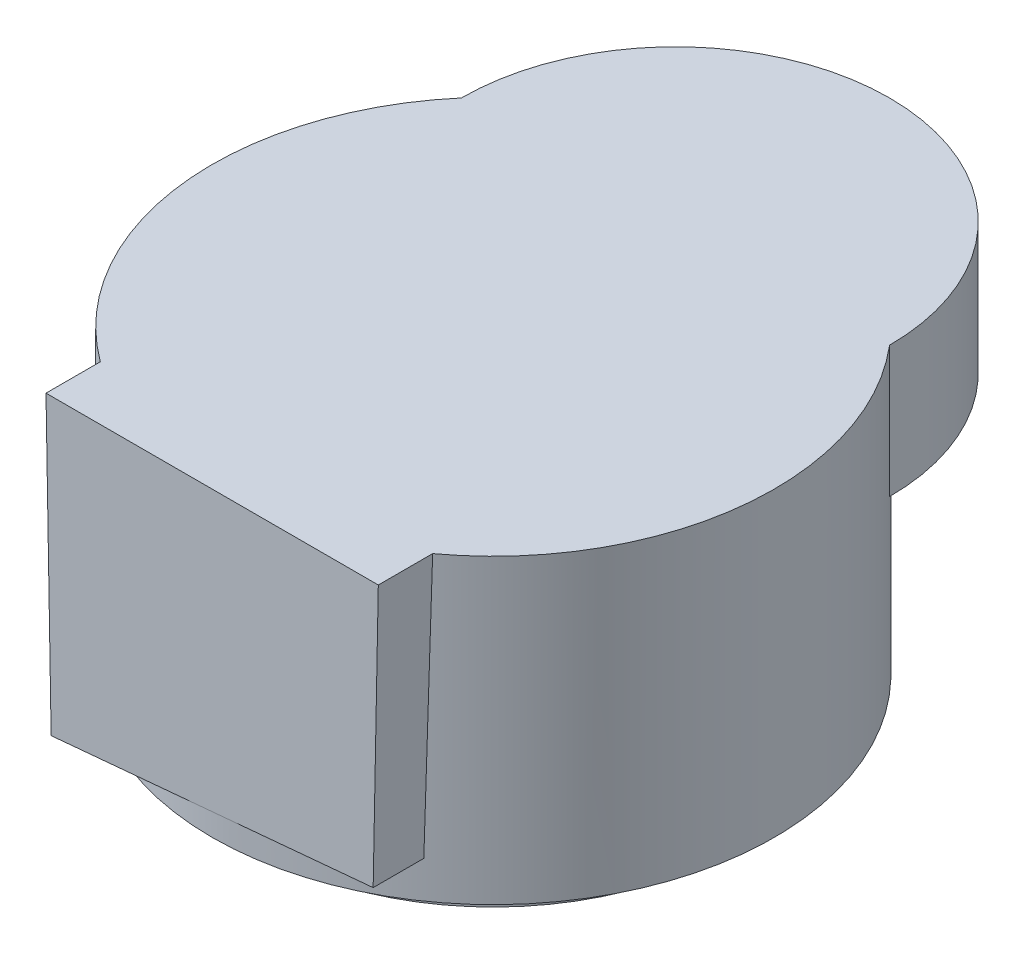
SolidWorks part; units mm, degrees
ref_plane "Alzado" through (0, 0, 0) normal (0, 0, 1) x (1, 0, 0)
ref_plane "Planta" through (0, 0, 0) normal (0, 1, 0) x (1, 0, 0)
ref_plane "Vista lateral" through (0, 0, 0) normal (1, 0, 0) x (0, 0, -1)
sketch "Croquis1" plane through (0, 0, 0) normal (0, 1, 0) x (1, 0, 0)
  circle A0 centre (0, 0) radius 9.56 construction
  circle A1 centre (0, 0) radius 8.035
  dimension "D1" = 19.12
  dimension "D2" = 16.07
extrude "Saliente-Extruir1" add sketch "Croquis1" along normal blind 1.15
sketch "Croquis2" plane through (0, 1.15, 0) normal (0, 1, 0) x (1, 0, 0)
  circle A0 centre (0, 0) radius 9.56 construction
  circle A1 centre (0, 0) radius 9.56
extrude "Saliente-Extruir2" add sketch "Croquis2" along normal blind 10.26
sketch "Croquis3" plane through (0, 11.41, 0) normal (0, 1, 0) x (1, 0, 0)
  arc A0 (-7.28, 6.1964) -> (7.28, 6.1964) centre (0, 6.1964) cw
  circle A1 centre (0, 0) radius 9.56 construction
  arc A2 (-7.28, 6.1964) -> (7.28, 6.1964) centre (0, 0) ccw
  dimension "D1" = 14.56
extrude "Saliente-Extruir3" add sketch "Croquis3" against normal blind 4.46
ref_plane "Plano1" through (0, 0, 9.56) normal (0, 0, 1) x (1, 0, 0)
sketch "Croquis6" plane through (0, 0, 9.56) normal (0, 0, 1) x (1, 0, 0)
  line L0 (-5.475, 1.41) -> (5.475, 2.41)
  line L1 (0, 0) -> (0, 15.1412) construction
  line L2 (5.475, 2.41) -> (5.65, 11.41)
  line L3 (-5.475, 1.41) -> (-5.65, 11.41)
  line L4 (9.56, 11.41) -> (-9.56, 11.41) construction
  line L5 (-5.65, 11.41) -> (5.65, 11.41)
  point P4 (0, 1.91)
  point P10 (0, 11.41)
  dimension "D1" = 10.95
  dimension "D2" = 11.3
  dimension "D3" = 10
  dimension "D4" = 9
extrude "Saliente-Extruir4" add sketch "Croquis6" against normal blind 4.46
ref_plane "Plano2" through (0, 0, 9.56) normal (0, 0, 1) x (1, 0, 0)
sketch "Croquis7" plane through (0, 0, 9.56) normal (0, 0, 1) x (1, 0, 0)
  line L0 (0, 0) -> (0, 12.5628) construction
  line L1 (-9.56, 6.28) -> (9.56, 6.28) construction
  line L2 (-9.56, 11.41) -> (-9.56, 1.15) construction
  line L3 (9.56, 1.15) -> (9.56, 11.41) construction
  line L5 (5.65, 11.41) -> (-5.65, 11.41)
  line L6 (-5.65, 11.41) -> (-5.475, 1.41)
  line L7 (-5.475, 1.41) -> (0, 1.91)
  line L8 (0, 1.91) -> (5.475, 2.41)
  line L9 (5.475, 2.41) -> (5.65, 11.41)
  line L10 (5.65, 11.41) -> (-5.65, 11.41)
  line L11 (-5.65, 11.41) -> (-5.475, 1.41)
  line L12 (-5.475, 1.41) -> (0, 1.91)
  line L13 (0, 1.91) -> (5.475, 2.41)
  line L14 (5.475, 2.41) -> (5.65, 11.41)
  point P13 (0, 6.2814)
  dimension "D1" = 0
ref_plane "Plano3" through (0, 0, 65.56) normal (0, 0, 1) x (1, 0, 0)
sketch "Croquis8" plane through (0, 0, 65.56) normal (0, 0, 1) x (1, 0, 0)
  line L1 (-3.55, 10.11) -> (3.55, 10.11)
  line L2 (-3.55, 10.11) -> (-3.55, 3.01)
  line L3 (-3.55, 3.01) -> (3.55, 3.01)
  line L4 (3.55, 10.11) -> (3.55, 3.01)
  line L5 (-3.55, 10.11) -> (3.55, 3.01) construction
  line L6 (-3.55, 3.01) -> (3.55, 10.11) construction
  line L7 (9.56, 1.15) -> (-9.56, 1.15)
  line L8 (9.56, 1.15) -> (-9.56, 1.15) construction
  point P0 (0, 6.56)
  point P10 (0, 10.11)
  dimension "D1" = 7.1
  dimension "D3" = 1.6
  dimension "D2" = 0
sketch "Croquis9" plane through (0, 0, 0) normal (1, 0, 0) x (0, 0, -1)
  line L0 (-9.56, 6.2814) -> (-65.56, 6.56) construction
  line L1 (-9.56, 12.5628) -> (-65.56, 10.11) construction
